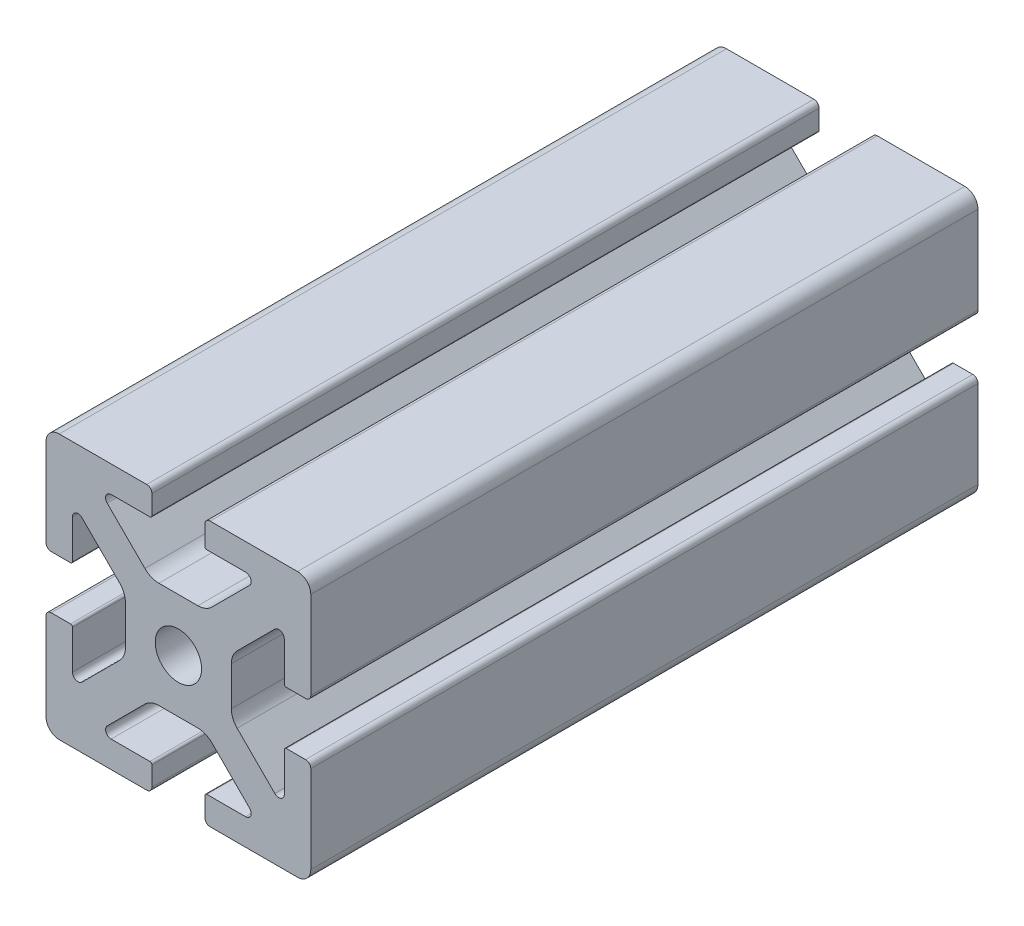
SolidWorks part; units mm, degrees
ref_plane "Front Plane" through (0, 0, 0) normal (0, 0, 1) x (1, 0, 0)
ref_plane "Top Plane" through (0, 0, 0) normal (0, 1, 0) x (1, 0, 0)
ref_plane "Right Plane" through (0, 0, 0) normal (1, 0, 0) x (0, 0, -1)
sketch "Sketch1" plane through (0, 0, 0) normal (0, 0, 1) x (1, 0, 0)
  line L0 (0, 20) -> (0, -20) construction
  line L1 (20, 0) -> (-20, 0) construction
  line L2 (-4, 20) -> (4, 20) construction
  line L3 (-11, 16) -> (11, 16) construction
  circle A0 centre (0, 0) radius 3.5 construction
  point P4 (0, 0)
  point P8 (0, 0)
  point P10 (0, 8)
  point P14 (0, 20)
  point P17 (0, 16)
  dimension "Thru Hole" = 7
  dimension "Height" = 40
  dimension "T Slot Depth" = 12
  dimension "T Slot Top Width" = 8
  dimension "T Slot Max Width" = 22
  dimension "Wall" = 4
sketch "Sketch2" plane through (0, 0, 0) normal (1, 0, 0) x (0, 0, -1)
  line L0 (50.4, 0) -> (-50.4, 0) construction
  point P4 (0, 0)
  dimension "D1" = 100.8
sketch "Sketch3" plane through (0, 0, 0) normal (0, 0, 1) x (1, 0, 0)
  line L0 (4.7874, 20) -> (18, 20)
  line L1 (20, 18) -> (20, -18) construction
  line L2 (18, -20) -> (-18, -20) construction
  line L3 (-20, 20) -> (20, -20) construction
  line L4 (4, 19.2126) -> (4, 16.3048)
  line L5 (-11, 16) -> (11, 16) construction
  line L6 (4.3048, 16) -> (10.1618, 16)
  line L7 (10.7545, 14.5691) -> (5.0641, 8.8787)
  line L8 (2.9428, 8) -> (-2.9428, 8)
  line L9 (0, 20) -> (0, -20) construction
  line L10 (11, 16) -> (11, 0) construction
  line L11 (20, 0) -> (-20, 0) construction
  line L12 (0, 0) -> (0, 20) construction
  line L13 (-4, 19.2126) -> (-4, 16.3048)
  line L14 (-10.7545, 14.5691) -> (-5.0641, 8.8787)
  line L15 (-4.3048, 16) -> (-10.1618, 16)
  line L16 (-4.7874, 20) -> (-18, 20)
  line L17 (0, 0) -> (-20, 0) construction
  line L18 (-20, 4.7874) -> (-20, 18)
  line L19 (-16, 4.3048) -> (-16, 10.1618)
  line L20 (-14.5691, 10.7545) -> (-8.8787, 5.0641)
  line L21 (-19.2126, 4) -> (-16.3048, 4)
  line L22 (-8, -2.9428) -> (-8, 2.9428)
  line L23 (-14.5691, -10.7545) -> (-8.8787, -5.0641)
  line L24 (-16, -4.3048) -> (-16, -10.1618)
  line L25 (-19.2126, -4) -> (-16.3048, -4)
  line L26 (-20, -4.7874) -> (-20, -18)
  line L27 (19.2126, -4) -> (16.3048, -4)
  line L28 (16, -4.3048) -> (16, -10.1618)
  line L29 (14.5691, -10.7545) -> (8.8787, -5.0641)
  line L30 (8, -2.9428) -> (8, 2.9428)
  line L31 (19.2126, 4) -> (16.3048, 4)
  line L32 (14.5691, 10.7545) -> (8.8787, 5.0641)
  line L33 (16, 4.3048) -> (16, 10.1618)
  line L34 (20, 18) -> (20, 4.7874)
  line L35 (20, -4.7874) -> (20, -18)
  line L36 (4.7874, -20) -> (18, -20)
  line L37 (-4.7874, -20) -> (-18, -20)
  line L38 (-14.5691, -10.7545) -> (-8.8787, -5.0641)
  line L39 (-4.3048, -16) -> (-10.1618, -16)
  line L40 (-10.7545, -14.5691) -> (-5.0641, -8.8787)
  line L41 (-4, -19.2126) -> (-4, -16.3048)
  line L42 (2.9428, -8) -> (-2.9428, -8)
  line L43 (10.7545, -14.5691) -> (5.0641, -8.8787)
  line L44 (4.3048, -16) -> (10.1618, -16)
  line L45 (4, -19.2126) -> (4, -16.3048)
  arc A0 (10.1618, 16) -> (10.7545, 14.5691) centre (10.1618, 15.1618) cw
  arc A1 (5.0641, 8.8787) -> (2.9428, 8) centre (2.9428, 11) cw
  circle A2 centre (0, 0) radius 3.5 construction
  circle A3 centre (0, 0) radius 3.5
  arc A4 (4.7874, 20) -> (4, 19.2126) centre (4.7874, 19.2126) ccw
  arc A5 (4, 16.3048) -> (4.3048, 16) centre (4.3048, 16.3048) ccw
  arc A6 (-4.7874, 20) -> (-4, 19.2126) centre (-4.7874, 19.2126) cw
  arc A7 (-10.1618, 16) -> (-10.7545, 14.5691) centre (-10.1618, 15.1618) ccw
  arc A8 (-5.0641, 8.8787) -> (-2.9428, 8) centre (-2.9428, 11) ccw
  arc A9 (-4, 16.3048) -> (-4.3048, 16) centre (-4.3048, 16.3048) cw
  arc A10 (-16.3048, 4) -> (-16, 4.3048) centre (-16.3048, 4.3048) ccw
  arc A11 (-8.8787, 5.0641) -> (-8, 2.9428) centre (-11, 2.9428) cw
  arc A12 (-16, 10.1618) -> (-14.5691, 10.7545) centre (-15.1618, 10.1618) cw
  arc A13 (-20, 4.7874) -> (-19.2126, 4) centre (-19.2126, 4.7874) ccw
  arc A14 (-16.3048, -4) -> (-16, -4.3048) centre (-16.3048, -4.3048) cw
  arc A15 (-20, -4.7874) -> (-19.2126, -4) centre (-19.2126, -4.7874) cw
  arc A16 (-8.8787, -5.0641) -> (-8, -2.9428) centre (-11, -2.9428) ccw
  arc A17 (-16, -10.1618) -> (-14.5691, -10.7545) centre (-15.1618, -10.1618) ccw
  arc A26 (-18, -20) -> (-20, -18) centre (-18, -18) cw
  arc A27 (-18, 20) -> (-20, 18) centre (-18, 18) ccw
  arc A28 (18, 20) -> (20, 18) centre (18, 18) cw
  arc A29 (20, -18) -> (18, -20) centre (18, -18) cw
  arc A30 (16, -10.1618) -> (14.5691, -10.7545) centre (15.1618, -10.1618) cw
  arc A31 (8.8787, -5.0641) -> (8, -2.9428) centre (11, -2.9428) cw
  arc A32 (20, -4.7874) -> (19.2126, -4) centre (19.2126, -4.7874) ccw
  arc A33 (16.3048, -4) -> (16, -4.3048) centre (16.3048, -4.3048) ccw
  arc A34 (20, 4.7874) -> (19.2126, 4) centre (19.2126, 4.7874) cw
  arc A35 (16, 10.1618) -> (14.5691, 10.7545) centre (15.1618, 10.1618) ccw
  arc A36 (8.8787, 5.0641) -> (8, 2.9428) centre (11, 2.9428) ccw
  arc A37 (16.3048, 4) -> (16, 4.3048) centre (16.3048, 4.3048) cw
  arc A38 (-4, -16.3048) -> (-4.3048, -16) centre (-4.3048, -16.3048) ccw
  arc A39 (-5.0641, -8.8787) -> (-2.9428, -8) centre (-2.9428, -11) cw
  arc A40 (-10.1618, -16) -> (-10.7545, -14.5691) centre (-10.1618, -15.1618) cw
  arc A41 (-4.7874, -20) -> (-4, -19.2126) centre (-4.7874, -19.2126) ccw
  arc A42 (4, -16.3048) -> (4.3048, -16) centre (4.3048, -16.3048) cw
  arc A43 (4.7874, -20) -> (4, -19.2126) centre (4.7874, -19.2126) cw
  arc A44 (5.0641, -8.8787) -> (2.9428, -8) centre (2.9428, -11) ccw
  arc A45 (10.1618, -16) -> (10.7545, -14.5691) centre (10.1618, -15.1618) ccw
  point P36 (4, 20)
  point P39 (4, 16)
  point P49 (0, 8)
  point P77 (-8, 0)
  point P78 (-16, -4)
  point P79 (-20, -4)
  point P104 (-20, -20)
  point P110 (20, 20)
  point P114 (20, -4)
  point P115 (16, -4)
  point P116 (8, 0)
  point P141 (0, -8)
  dimension "D1" = 3
  dimension "D2" = 0.8382
  dimension "D4" = 0.7874
  dimension "D5" = 0.3048
  dimension "D6" = 2
  dimension "D3" = 45
extrude "Boss-Extrude1" add sketch "Sketch3" along normal up to vertex (50.4 mm away) and the other way up to vertex (50.4 mm away) contours A45 L44 A42 L45 A43 L36 A29 L35 A32 L27 A33 L28 A30 L29 A31 L30 A36 L32 A35 L33 A37 L31 A34 L34 A28 L0 A4 L4 A5 L6 A0 L7 A1 L8 A8 L14 A7 L15 A9 L13 A6 L16 A27 L18 A13 L21 A10 L19 A12 L20 A11 up to point (0, 0, 50.4) other way up to point (0, 0, -50.4)
